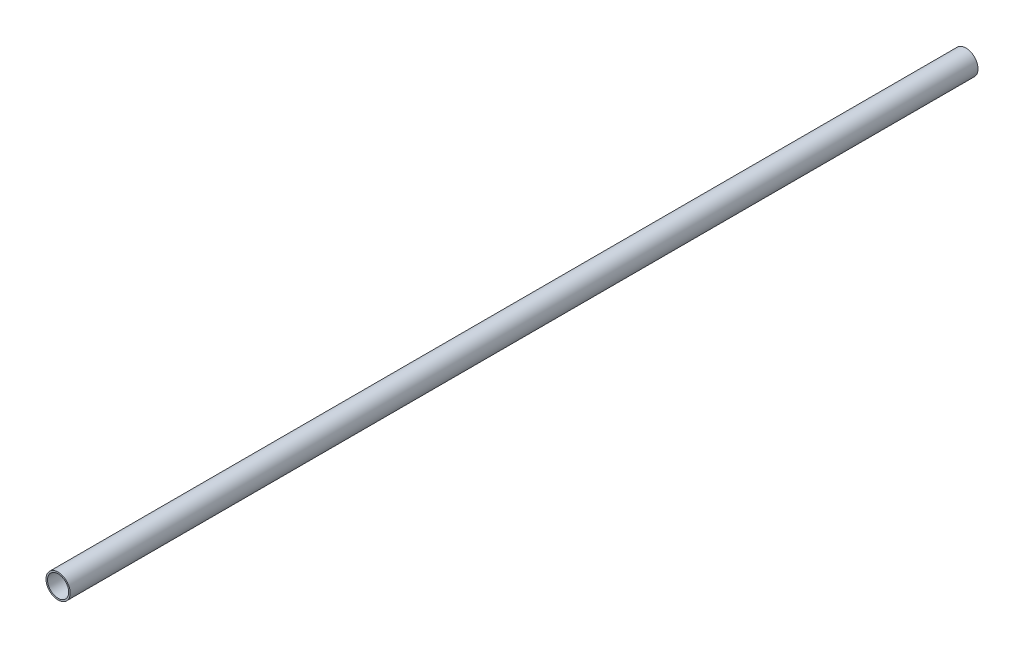
SolidWorks part; units mm, degrees
material "Thornel Mat VMA"
ref_plane "Front Plane" through (0, 0, 0) normal (0, 0, 1) x (1, 0, 0)
ref_plane "Top Plane" through (0, 0, 0) normal (0, 1, 0) x (1, 0, 0)
ref_plane "Right Plane" through (0, 0, 0) normal (1, 0, 0) x (0, 0, -1)
sketch "Sketch1" plane through (0, 0, 0) normal (0, 0, 1) x (1, 0, 0)
  circle A0 centre (0, 0) radius 8
  circle A1 centre (0, 0) radius 7
  dimension "D1" = 16
  dimension "D2" = 1
extrude "Boss-Extrude1" add sketch "Sketch1" along normal blind 600
